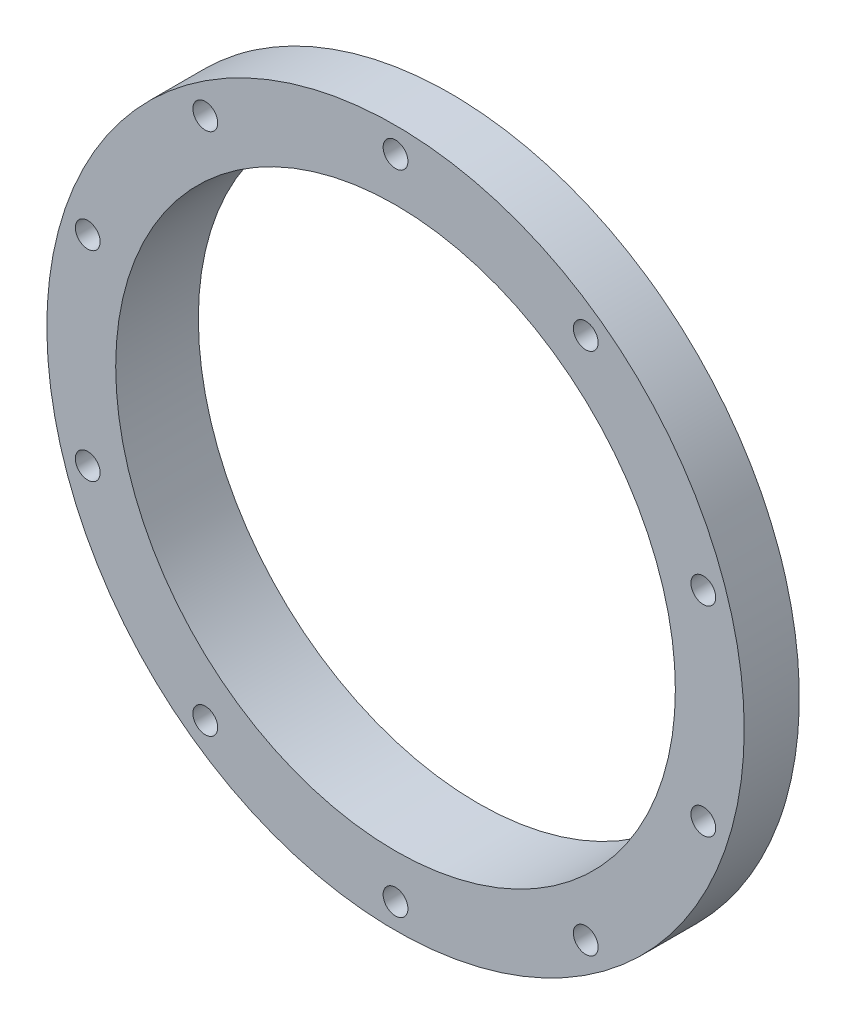
SolidWorks part; units mm, degrees
ref_plane "Front Plane" through (0, 0, 0) normal (0, 0, 1) x (1, 0, 0)
ref_plane "Top Plane" through (0, 0, 0) normal (0, 1, 0) x (1, 0, 0)
ref_plane "Right Plane" through (0, 0, 0) normal (1, 0, 0) x (0, 0, -1)
sketch "Sketch1" plane through (0, 0, 0) normal (0, 0, 1) x (1, 0, 0)
  circle A0 centre (0, 0) radius 101.6
  circle A1 centre (0, 0) radius 126.6
  dimension "D1" = 203.2
  dimension "D2" = 253.2
extrude "Boss-Extrude1" add sketch "Sketch1" along normal blind 30
sketch "Sketch5" plane through (0, 0, 0) normal (1, 0, 0) x (0, 0, -1)
  line L0 (0, 126.6) -> (-10, 126.6)
  line L1 (0, 126.6) -> (-30, 126.6) construction
  line L2 (-10, 126.6) -> (0, 111.6)
  line L3 (0, -126.6) -> (0, 126.6) construction
  line L4 (0, 111.6) -> (0, 126.6)
  line L5 (-30, 126.6) -> (-30, -126.6) construction
  dimension "D1" = 15
  dimension "D2" = 20
revolve "Cut-Revolve1" cut sketch "Sketch5" angle 360 about axis through (0, 0, 30) along (0, 0, -1)
sketch "Sketch6" plane through (0, 0, 30) normal (0, 0, 1) x (1, 0, 0)
  circle A0 centre (0, 0) radius 117.5 construction
  point P4 (0, 117.5)
  dimension "D1" = 235
ref_plane "Plane1" through (0, 0, 0) normal (0, 0, -1) x (-1, 0, 0)
sketch "Sketch10" plane through (0, 0, 0) normal (0, 0, -1) x (-1, 0, 0)
  circle A0 centre (0, 0) radius 114.1 construction
  circle A1 centre (0, 117.5) radius 4.5
  dimension "D1" = 228.2
  dimension "D2" = 9
extrude "Cut-Extrude1" cut sketch "Sketch10" against normal blind 40
sketch "Sketch11" plane through (0, 0, 0) normal (0, 0, -1) x (-1, 0, 0)
  circle A0 centre (0, 117.5) radius 10
  circle A1 centre (0, 0) radius 117.5 construction
  dimension "D1" = 20
extrude "Cut-Extrude2" cut sketch "Sketch11" against normal blind 10
pattern_circular "CirPattern1" count 10 over 360 about axis through (0, 0, 0) along (0, 0, 1) of "Cut-Extrude1", "Cut-Extrude2"
